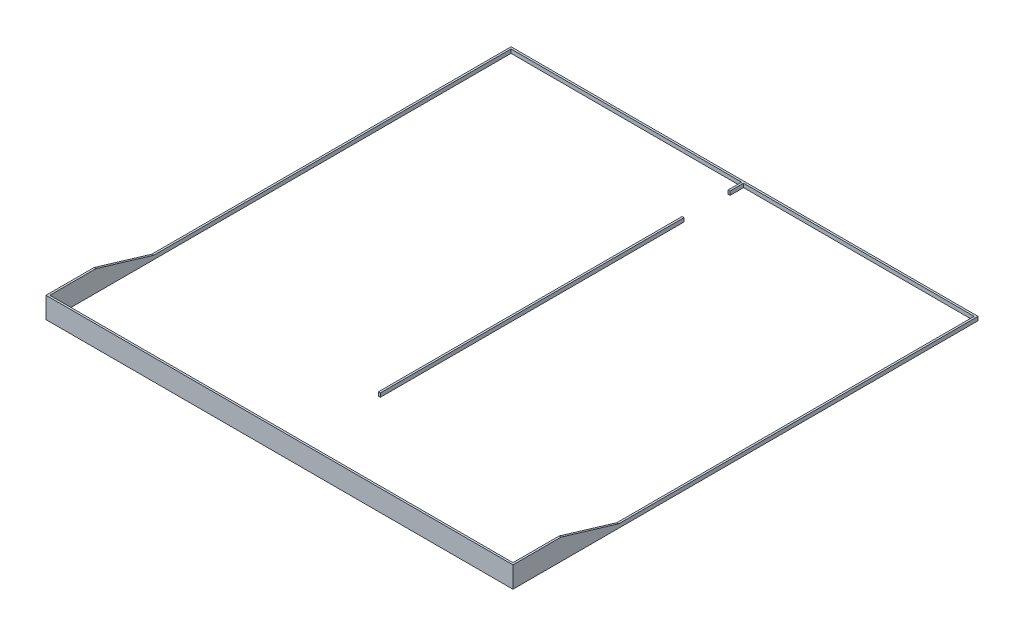
SolidWorks part; units mm, degrees
ref_plane "前视基准面" through (0, 0, 0) normal (0, 0, 1) x (1, 0, 0)
ref_plane "上视基准面" through (0, 0, 0) normal (0, 1, 0) x (1, 0, 0)
ref_plane "右视基准面" through (0, 0, 0) normal (1, 0, 0) x (0, 0, -1)
other "Configuration Table"
sketch "草图1" plane through (0, 0, 0) normal (0, 1, 0) x (1, 0, 0)
  line L0 (-25, 5650) -> (25, 5650)
  line L1 (-6075, 6050) -> (6075, 6050)
  line L2 (-6075, 6050) -> (-6075, -6050)
  line L3 (-6075, -6050) -> (6075, -6050)
  line L4 (6075, 6050) -> (6075, -6050)
  line L5 (-6025, 6000) -> (-25, 6000)
  line L6 (-6025, 6000) -> (-6025, -6000)
  line L7 (-6025, -6000) -> (6025, -6000)
  line L8 (-25, 6000) -> (-25, 5650)
  line L10 (25, 5650) -> (25, 6000)
  line L11 (25, 6000) -> (6025, 6000)
  line L12 (6025, -6000) -> (6025, 6000)
  line L14 (-25, 4450) -> (25, 4450)
  line L15 (-25, 4450) -> (-25, -3450)
  line L16 (-25, -3450) -> (25, -3450)
  line L17 (25, 4450) -> (25, -3450)
  dimension "D1" = 50
  dimension "D2" = 50
  dimension "D3" = 50
  dimension "D4" = 25
  dimension "D5" = 6000
  dimension "D6" = 350
  dimension "D7" = 50
  dimension "D8" = 6000
  dimension "D9" = 1200
  dimension "D10" = 2550
  dimension "D11" = 50
  dimension "D12" = 12000
extrude "凸台-拉伸1" add sketch "草图1" along normal blind 550 contours L4 L1 L2 L3 L12 L7 L6 L5 L8 L0 L10 L11 | L17 L14 L15 L16
sketch "草图2" plane through (6075, 0, 0) normal (1, 0, 0) x (0, 0, -1)
  line L0 (-4800, 550) -> (-3300, 100)
  line L1 (6050, 550) -> (-6050, 550) construction
  line L2 (-3300, 100) -> (6050, 100)
  line L3 (6050, 550) -> (6050, 0) construction
  line L4 (6050, 100) -> (6050, 550)
  line L5 (6050, 550) -> (-4800, 550)
  line L6 (6050, 0) -> (-6050, 0) construction
  line L7 (-6050, 550) -> (-6050, 0) construction
  dimension "D1" = 100
  dimension "D2" = 2750
  dimension "D3" = 1250
extrude "切除-拉伸1" cut sketch "草图2" against normal through all
sketch "草图3" plane through (-25, 0, 0) normal (-1, 0, 0) x (0, 0, 1)
  line L0 (3300, 100) -> (-6050, 100) construction
  line L1 (3450, 550) -> (-4450, 550)
  line L2 (3450, 550) -> (3450, 100)
  line L3 (3450, 100) -> (-4450, 100)
  line L4 (-4450, 550) -> (-4450, 100)
  line L5 (-4450, 550) -> (-4450, 0) construction
extrude "切除-拉伸2" cut sketch "草图3" against normal through all
